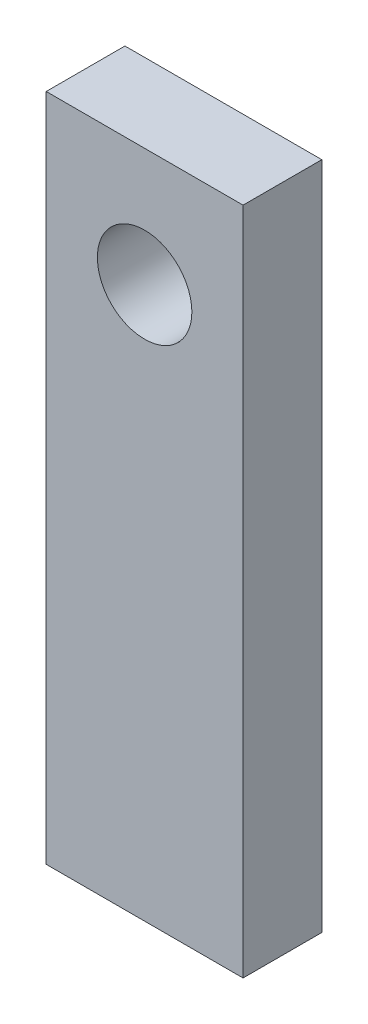
SolidWorks part; units mm, degrees
material "2024-T3"
ref_plane "正面" through (0, 0, 0) normal (0, 0, 1) x (1, 0, 0)
ref_plane "平面" through (0, 0, 0) normal (0, 1, 0) x (1, 0, 0)
ref_plane "右側面" through (0, 0, 0) normal (1, 0, 0) x (0, 0, -1)
sketch "ｽｹｯﾁ1" plane through (0, 0, 0) normal (0, 1, 0) x (1, 0, 0)
  line L1 (0, 0) -> (25, 0)
  line L2 (0, 0) -> (0, 10)
  line L3 (0, 10) -> (25, 10)
  line L4 (25, 0) -> (25, 10)
  dimension "D1" = 10
  dimension "D2" = 25
extrude "ﾎﾞｽ - 押し出し1" add sketch "ｽｹｯﾁ1" along normal blind 85
sketch "ｽｹｯﾁ2" plane through (0, 0, 0) normal (0, 0, 1) x (1, 0, 0)
  line L0 (0, 85) -> (0, 0) construction
  line L1 (0, 0) -> (25, 0) construction
  circle A0 centre (12.5, 70) radius 6
  dimension "D1" = 12
  dimension "D2" = 12.5
  dimension "D3" = 70
extrude "ｶｯﾄ - 押し出し1" cut sketch "ｽｹｯﾁ2" against normal through all
sketch "ｽｹｯﾁ3" plane through (0, 0, 0) normal (0, -1, 0) x (1, 0, 0)
  line L0 (0, -5) -> (25, -5)
  line L1 (0, -10) -> (0, 0) construction
  line L2 (25, 0) -> (25, -10) construction
  point P6 (5, -5)
  point P8 (20, -5)
  dimension "D1" = 5
  dimension "D2" = 5
hole_wizard "M3x0.5 ねじ穴1" positions "ｽｹｯﾁ3" profile "ｽｹｯﾁ4" tap size "M3x0.5" standard "JIS"
sketch "ｽｹｯﾁ4" plane through (20, 0, -5) normal (1, 0, 0) x (0, 0, -1)
  line L0 (0, 0) -> (0, 12.2511)
  line L1 (0, 12.2511) -> (1.25, 11.5)
  line L2 (1.25, 11.5) -> (1.25, 0)
  line L5 (1.25, 0) -> (0, 0)
  line L10 (0, 12.2511) -> (-1.25, 11.5) construction
  line L11 (0, -6.35) -> (0, 107.95) construction
  dimension "ねじ下穴ﾄﾞﾘﾙ直径" = 2.5
  dimension "ねじ下穴ﾄﾞﾘﾙの深さ" = 11.5
  dimension "ﾄﾞﾘﾙ角度" = 118
cosmetic thread "穴のねじ山1" parameters "D1"=10, "D2"=3
cosmetic thread "穴のねじ山2" parameters "D1"=10, "D2"=3
